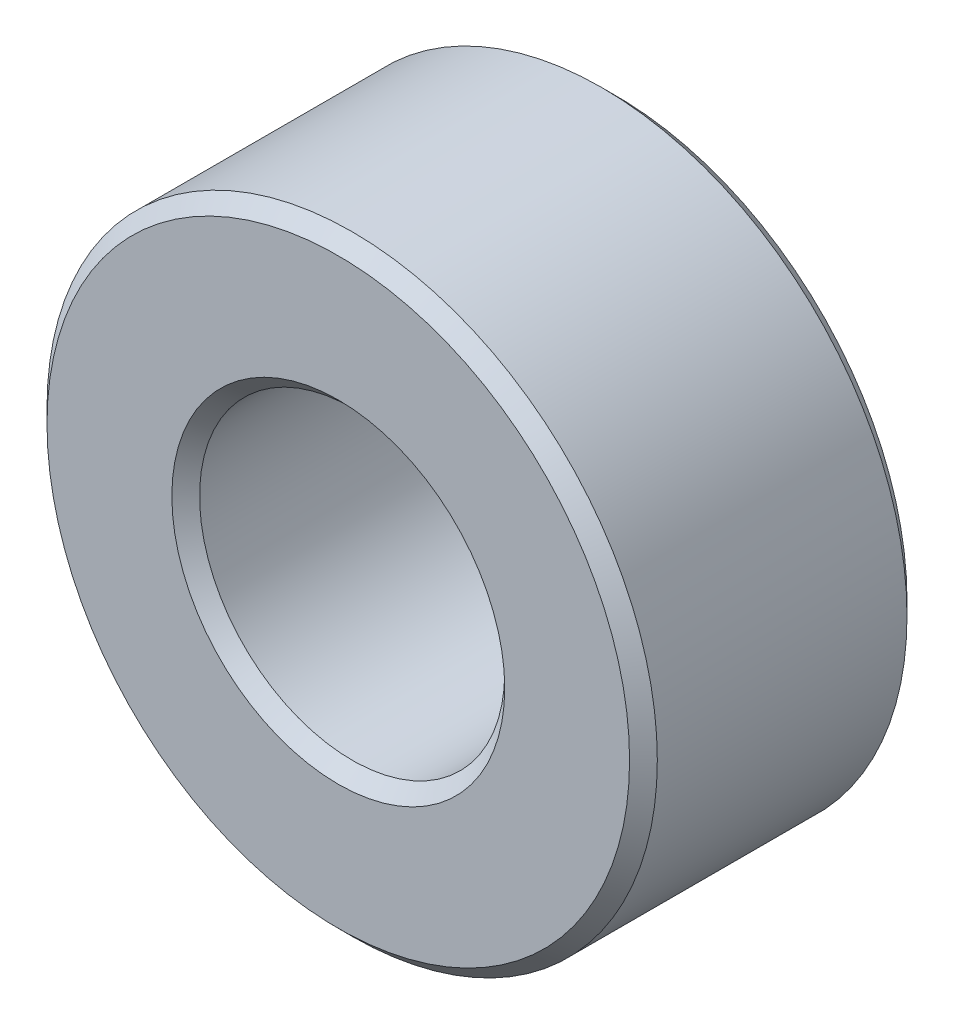
SolidWorks part; units mm, degrees
material "PET"
ref_plane "Přední rovina" through (0, 0, 0) normal (0, 0, 1) x (1, 0, 0)
ref_plane "Horní rovina" through (0, 0, 0) normal (0, 1, 0) x (1, 0, 0)
ref_plane "Pravá rovina" through (0, 0, 0) normal (1, 0, 0) x (0, 0, -1)
sketch "Skica1" plane through (0, 0, 0) normal (0, 0, 1) x (1, 0, 0)
  circle A0 centre (0, 0) radius 11
  circle A1 centre (0, 0) radius 5.5
  dimension "D1" = 11
  dimension "D2" = 22
extrude "Přidat vysunutím1" add sketch "Skica1" along normal blind 10
chamfer "Zkosení1" distance 0.5 angle 45 4 edges at (5.5, 0, 0) (5.5, 0, 10) (11, 0, 0) (11, 0, 10)
